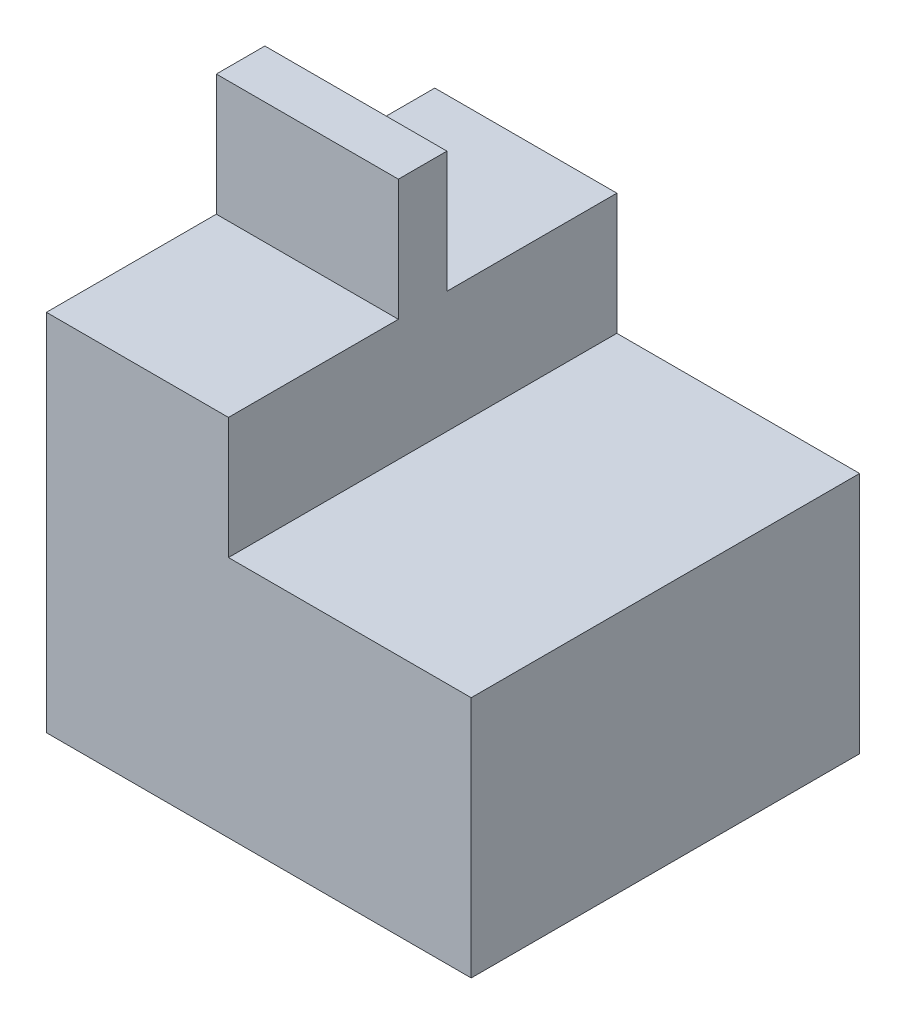
SolidWorks part; units mm, degrees
ref_plane "Front Plane" through (0, 0, 0) normal (0, 0, 1) x (1, 0, 0)
ref_plane "Top Plane" through (0, 0, 0) normal (0, 1, 0) x (1, 0, 0)
ref_plane "Right Plane" through (0, 0, 0) normal (1, 0, 0) x (0, 0, -1)
sketch "Sketch1" plane through (0, 0, 0) normal (0, 0, 1) x (1, 0, 0)
  line L0 (-36.0322, 32.8779) -> (-51.0322, 32.8779)
  line L1 (-51.0322, 32.8779) -> (-51.0322, -7.1221)
  line L2 (-51.0322, -7.1221) -> (-16.0322, -7.1221)
  line L3 (-16.0322, -7.1221) -> (-16.0322, 12.8779)
  line L4 (-16.0322, 12.8779) -> (-36.0322, 12.8779)
  line L5 (-36.0322, 12.8779) -> (-36.0322, 32.8779)
  dimension "D1" = 15
  dimension "D2" = 35
  dimension "D3" = 20
  dimension "D4" = 20
  dimension "D5" = 40
extrude "Boss-Extrude1" add sketch "Sketch1" along normal blind 32
sketch "Sketch2" plane through (-36.0322, 0, 0) normal (1, 0, 0) x (0, 0, -1)
  line L0 (-32, -7.1221) -> (0, -7.1221) construction
  line L1 (0, 32.8779) -> (-14, 32.8779)
  line L2 (0, 32.8779) -> (0, 22.8779)
  line L3 (0, 22.8779) -> (-14, 22.8779)
  line L4 (-14, 32.8779) -> (-14, 22.8779)
  line L5 (-32, 32.8779) -> (-18, 32.8779)
  line L6 (-32, 32.8779) -> (-32, 22.8779)
  line L7 (-32, 22.8779) -> (-18, 22.8779)
  line L8 (-18, 32.8779) -> (-18, 22.8779)
  line L9 (-10, -12.1221) -> (-22, -12.1221)
  line L10 (-10, -12.1221) -> (-10, -2.1221)
  line L11 (-10, -2.1221) -> (-22, -2.1221)
  line L12 (-22, -12.1221) -> (-22, -2.1221)
  line L13 (-10, -12.1221) -> (-22, -2.1221) construction
  line L14 (-10, -2.1221) -> (-22, -12.1221) construction
  point P10 (-16, -7.1221)
  dimension "D1" = 14
  dimension "D2" = 14
  dimension "D3" = 10
  dimension "D4" = 10
  dimension "D5" = 12
  dimension "D6" = 10
extrude "Cut-Extrude1" cut sketch "Sketch2" against normal through all
